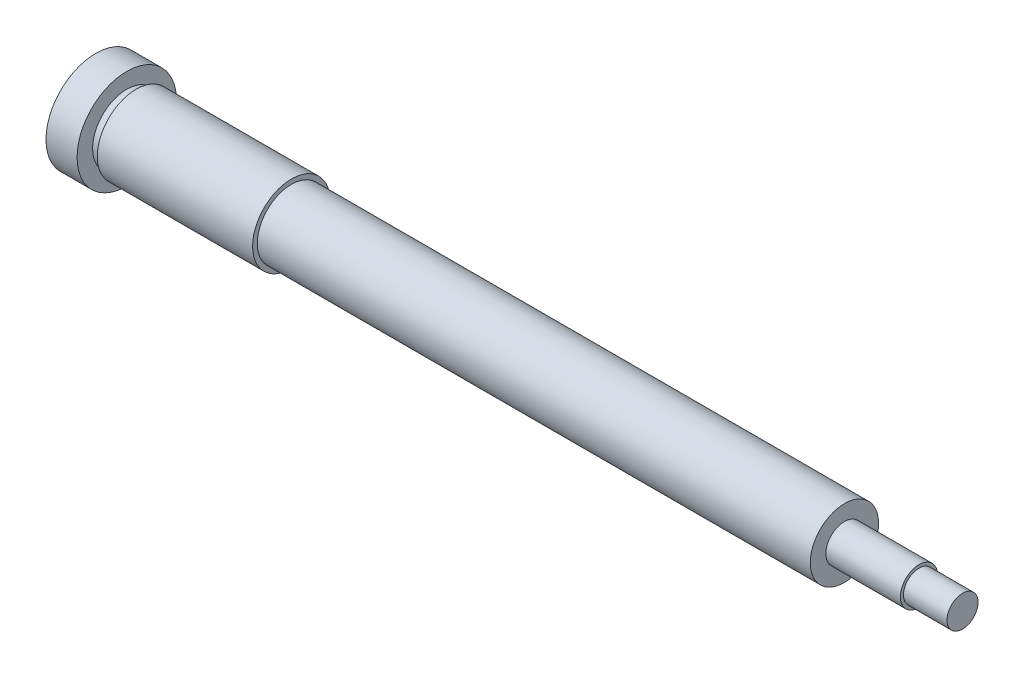
SolidWorks part; units mm, degrees
ref_plane "Front Plane" through (0, 0, 0) normal (0, 0, 1) x (1, 0, 0)
ref_plane "Top Plane" through (0, 0, 0) normal (0, 1, 0) x (1, 0, 0)
ref_plane "Right Plane" through (0, 0, 0) normal (1, 0, 0) x (0, 0, -1)
sketch "Sketch1" plane through (0, 0, 0) normal (0, 0, 1) x (1, 0, 0)
  line L1 (-279, 0) -> (-279, 16)
  line L2 (-279, 16) -> (-269, 16)
  line L3 (-269, 16) -> (-269, 11)
  line L4 (-269, 11) -> (-266, 11)
  line L5 (-266, 11) -> (-266, 12.5)
  line L6 (-266, 12.5) -> (-216, 12.5)
  line L7 (-216, 12.5) -> (-216, 11)
  line L8 (-216, 11) -> (-38, 11)
  line L9 (-38, 11) -> (-38, 6)
  line L10 (-38, 6) -> (-14, 6)
  line L11 (-14, 6) -> (-14, 5)
  line L12 (-14, 5) -> (0, 5)
  line L13 (0, 5) -> (0, 0)
  line L14 (-279, 0) -> (0, 0) construction
  line L15 (0, 0) -> (-279, 0)
  dimension "D1" = 10
  dimension "D2" = 3
  dimension "D3" = 14
  dimension "D4" = 24
  dimension "D5" = 50
  dimension "D6" = 178
  dimension "D7" = 32
  dimension "D8" = 22
  dimension "D9" = 25
  dimension "D10" = 22
  dimension "D11" = 12
  dimension "D12" = 10
revolve "Revolve1" add sketch "Sketch1" angle 360 about L14
cosmetic thread "Cosmetic Thread1" parameters "D2"=22.344
cosmetic thread "Cosmetic Thread2" parameters "D2"=8.344
